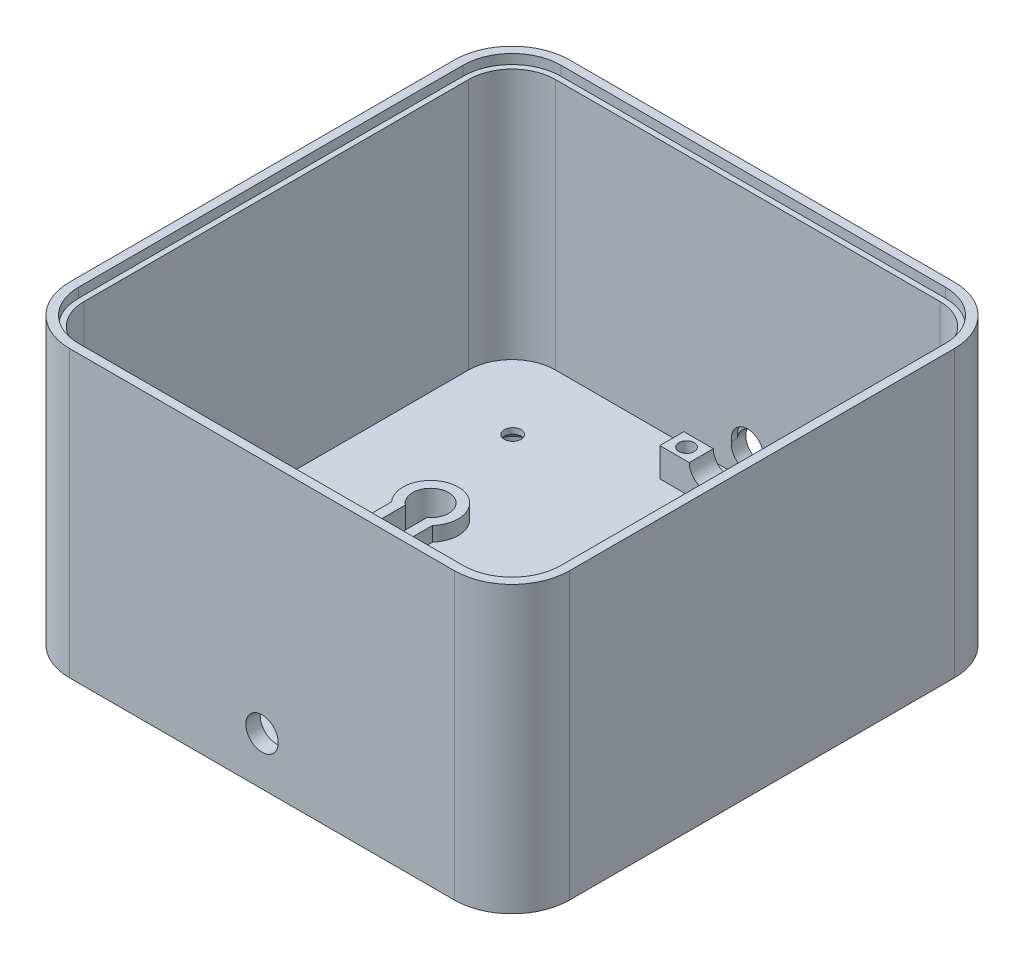
SolidWorks part; units mm, degrees
ref_plane "Alzado" through (0, 0, 0) normal (0, 0, 1) x (1, 0, 0)
ref_plane "Planta" through (0, 0, 0) normal (0, 1, 0) x (1, 0, 0)
ref_plane "Vista lateral" through (0, 0, 0) normal (1, 0, 0) x (0, 0, -1)
sketch "Croquis1" plane through (0, 0, 0) normal (0, 1, 0) x (1, 0, 0)
  line L1 (12, 0) -> (92, 0)
  line L2 (0, 12) -> (0, 92)
  line L3 (12, 104) -> (92, 104)
  line L4 (104, 12) -> (104, 92)
  arc A0 (12, 0) -> (0, 12) centre (12, 12) cw
  arc A1 (92, 0) -> (104, 12) centre (92, 12) ccw
  arc A2 (92, 104) -> (104, 92) centre (92, 92) cw
  arc A3 (0, 92) -> (12, 104) centre (12, 92) cw
  point P7 (0, 0)
  point P10 (104, 0)
  point P15 (0, 104)
  dimension "D3" = 12
  dimension "D1" = 104
  dimension "D2" = 104
extrude "Saliente-Extruir1" add sketch "Croquis1" along normal blind 5
sketch "Croquis2" plane through (0, 5, 0) normal (0, 1, 0) x (1, 0, 0)
  line L0 (12, 3) -> (92, 3)
  line L1 (101, 12) -> (101, 92)
  line L2 (92, 101) -> (12, 101)
  line L3 (3, 92) -> (3, 12)
  line L4 (12, 0) -> (92, 0)
  line L5 (104, 12) -> (104, 92)
  line L6 (92, 104) -> (12, 104)
  line L7 (0, 92) -> (0, 12)
  line L8 (12, 0) -> (92, 0)
  line L9 (104, 12) -> (104, 92)
  line L10 (92, 104) -> (12, 104)
  line L11 (0, 92) -> (0, 12)
  arc A0 (3, 12) -> (12, 3) centre (12, 12) ccw
  arc A1 (92, 3) -> (101, 12) centre (92, 12) ccw
  arc A2 (101, 92) -> (92, 101) centre (92, 92) ccw
  arc A3 (12, 101) -> (3, 92) centre (12, 92) ccw
  arc A4 (0, 12) -> (12, 0) centre (12, 12) ccw
  arc A5 (92, 0) -> (104, 12) centre (92, 12) ccw
  arc A6 (104, 92) -> (92, 104) centre (92, 92) ccw
  arc A7 (12, 104) -> (0, 92) centre (12, 92) ccw
  arc A8 (0, 12) -> (12, 0) centre (12, 12) ccw
  arc A9 (92, 0) -> (104, 12) centre (92, 12) ccw
  arc A10 (104, 92) -> (92, 104) centre (92, 92) ccw
  arc A11 (12, 104) -> (0, 92) centre (12, 92) ccw
  dimension "D1" = 0
  dimension "D2" = 3
extrude "Saliente-Extruir2" add sketch "Croquis2" along normal blind 54.34
sketch "Croquis3" plane through (0, 59.34, 0) normal (0, 1, 0) x (1, 0, 0)
  line L0 (12, 1.85) -> (92, 1.85)
  line L1 (102.15, 12) -> (102.15, 92)
  line L2 (92, 102.15) -> (12, 102.15)
  line L3 (1.85, 92) -> (1.85, 12)
  line L4 (12, 0) -> (92, 0)
  line L5 (104, 12) -> (104, 92)
  line L6 (92, 104) -> (12, 104)
  line L7 (0, 92) -> (0, 12)
  line L8 (12, 0) -> (92, 0)
  line L9 (104, 12) -> (104, 92)
  line L10 (92, 104) -> (12, 104)
  line L11 (0, 92) -> (0, 12)
  arc A0 (1.85, 12) -> (12, 1.85) centre (12, 12) ccw
  arc A1 (92, 1.85) -> (102.15, 12) centre (92, 12) ccw
  arc A2 (102.15, 92) -> (92, 102.15) centre (92, 92) ccw
  arc A3 (12, 102.15) -> (1.85, 92) centre (12, 92) ccw
  arc A4 (0, 12) -> (12, 0) centre (12, 12) ccw
  arc A5 (92, 0) -> (104, 12) centre (92, 12) ccw
  arc A6 (104, 92) -> (92, 104) centre (92, 92) ccw
  arc A7 (12, 104) -> (0, 92) centre (12, 92) ccw
  arc A8 (0, 12) -> (12, 0) centre (12, 12) ccw
  arc A9 (92, 0) -> (104, 12) centre (92, 12) ccw
  arc A10 (104, 92) -> (92, 104) centre (92, 92) ccw
  arc A11 (12, 104) -> (0, 92) centre (12, 92) ccw
  dimension "D1" = 0
  dimension "D2" = 1.85
extrude "Cortar-Extruir1" cut sketch "Croquis3" against normal blind 2 contours A0 L0 A1 L1 A2 L2 A3 L3
sketch "Croquis4" plane through (0, 0, 0) normal (0, -1, 0) x (1, 0, 0)
  line L0 (0, 0) -> (26, 0) construction
  line L1 (12, 0) -> (92, 0) construction
  line L2 (26, 0) -> (26, -50.33) construction
  line L3 (52, 0) -> (52, -86.7959) construction
  line L4 (23.75, -50.33) -> (23.75, -58.07)
  line L5 (28.25, -50.33) -> (28.25, -58.07)
  line L6 (75.75, -50.33) -> (75.75, -58.07)
  line L7 (80.25, -50.33) -> (80.25, -58.07)
  arc A0 (23.75, -58.07) -> (28.25, -58.07) centre (26, -61.07) ccw
  arc A1 (28.25, -50.33) -> (23.75, -50.33) centre (26, -50.33) ccw
  arc A2 (80.25, -58.07) -> (75.75, -58.07) centre (78, -61.07) cw
  arc A3 (75.75, -50.33) -> (80.25, -50.33) centre (78, -50.33) cw
  dimension "D1" = 26
  dimension "D2" = 61.07
extrude "Cortar-Extruir2" cut sketch "Croquis4" against normal blind 17
sketch "Croquis5" plane through (0, 5, 0) normal (0, 1, 0) x (1, 0, 0)
  line L0 (23.75, 50.33) -> (23.75, 58.07) construction
  line L1 (28.25, 58.07) -> (28.25, 50.33) construction
  line L2 (80.25, 58.07) -> (80.25, 50.33) construction
  line L3 (75.75, 50.33) -> (75.75, 58.07) construction
  line L20 (23.75, 50.33) -> (23.75, 58.07)
  line L21 (28.25, 58.07) -> (28.25, 50.33)
  line L22 (80.25, 58.07) -> (80.25, 50.33)
  line L23 (75.75, 50.33) -> (75.75, 58.07)
  line L24 (73.75, 50.33) -> (73.75, 57.197)
  line L25 (82.25, 57.197) -> (82.25, 50.33)
  line L26 (21.75, 50.33) -> (21.75, 57.197)
  line L27 (30.25, 57.197) -> (30.25, 50.33)
  arc A0 (23.75, 50.33) -> (28.25, 50.33) centre (26, 50.33) ccw construction
  arc A1 (28.25, 58.07) -> (23.75, 58.07) centre (26, 61.07) ccw construction
  arc A2 (80.25, 58.07) -> (75.75, 58.07) centre (78, 61.07) ccw construction
  arc A3 (75.75, 50.33) -> (80.25, 50.33) centre (78, 50.33) ccw construction
  arc A20 (23.75, 50.33) -> (28.25, 50.33) centre (26, 50.33) ccw
  arc A21 (28.25, 58.07) -> (23.75, 58.07) centre (26, 61.07) ccw
  arc A22 (80.25, 58.07) -> (75.75, 58.07) centre (78, 61.07) ccw
  arc A23 (75.75, 50.33) -> (80.25, 50.33) centre (78, 50.33) ccw
  arc A24 (82.25, 57.197) -> (73.75, 57.197) centre (78, 61.07) ccw
  arc A25 (73.75, 50.33) -> (82.25, 50.33) centre (78, 50.33) ccw
  arc A26 (30.25, 57.197) -> (21.75, 57.197) centre (26, 61.07) ccw
  arc A27 (21.75, 50.33) -> (30.25, 50.33) centre (26, 50.33) ccw
  dimension "D1" = 2
extrude "Saliente-Extruir3" add sketch "Croquis5" along normal blind 3
sketch "Croquis6" plane through (0, 5, 0) normal (0, 1, 0) x (1, 0, 0)
  line L0 (14.8757, 40.1901) -> (34.6757, 40.1901)
  line L1 (16.8757, 38.1901) -> (32.6757, 38.1901)
  line L2 (16.8757, 38.1901) -> (16.8757, 11.3901)
  line L3 (16.8757, 11.3901) -> (32.6757, 11.3901)
  line L5 (34.6757, 40.1901) -> (34.6757, 38.1901)
  line L6 (14.8757, 9.3901) -> (34.6757, 9.3901)
  line L7 (14.8757, 40.1901) -> (14.8757, 9.3901)
  line L10 (32.6757, 38.1901) -> (34.6757, 38.1901)
  line L11 (32.6757, 11.3901) -> (34.6757, 11.3901)
  line L12 (34.6757, 11.3901) -> (34.6757, 9.3901)
  line L13 (34.6757, 40.1901) -> (34.6757, 9.3901) construction
  line L14 (32.6757, 38.1901) -> (32.6757, 11.3901) construction
  dimension "D1" = 15.8
  dimension "D2" = 26.8
  dimension "D3" = 2
extrude "Saliente-Extruir4" add sketch "Croquis6" along normal blind 15
sketch "Croquis8" plane through (0, 5, 0) normal (0, 1, 0) x (1, 0, 0)
  line L0 (52, 3) -> (52, 18.8903) construction
  line L1 (12, 3) -> (92, 3) construction
  line L2 (42.5, 18.8903) -> (61.5, 18.8903)
  line L3 (61.5, 18.8903) -> (61.5, 23.8903)
  line L4 (61.5, 23.8903) -> (42.5, 23.8903)
  line L5 (52, 23.8903) -> (52, 18.8903) construction
  line L6 (42.5, 18.8903) -> (42.5, 23.8903)
  dimension "D1" = 5
  dimension "D2" = 9.5
extrude "Saliente-Extruir5" add sketch "Croquis8" along normal blind 6
sketch "Croquis10" plane through (0, 0, -23.8903) normal (0, 0, -1) x (-1, 0, 0)
  line L0 (-61.5, 11) -> (-42.5, 11) construction
  circle A0 centre (-52, 11) radius 3.3758
extrude "Cortar-Extruir3" cut sketch "Croquis10" against normal blind 10
sketch "Croquis11" plane through (0, 11, 0) normal (0, 1, 0) x (1, 0, 0)
  line L0 (55.3758, 21.3903) -> (61.5, 21.3903) construction
  line L1 (55.3758, 23.8903) -> (55.3758, 18.8903) construction
  line L2 (61.5, 18.8903) -> (61.5, 23.8903) construction
  line L3 (52, 23.8903) -> (52, 18.8903) construction
  line L4 (55.3758, 23.8903) -> (48.6242, 23.8903) construction
  line L5 (48.6242, 18.8903) -> (55.3758, 18.8903) construction
  circle A0 centre (58.4379, 21.3903) radius 1.6
  circle A1 centre (45.5621, 21.3903) radius 1.6
extrude "Cortar-Extruir4" cut sketch "Croquis11" against normal blind 9
sketch "Croquis12" plane through (0, 0, -3) normal (0, 0, -1) x (-1, 0, 0)
  circle A0 centre (-52, 10) radius 3.3758
extrude "Cortar-Extruir5" cut sketch "Croquis12" against normal blind 9 and the other way blind 138
ref_plane "Plano1" through (0, 0, -58.07) normal (0, 0, -1) x (-1, 0, 0)
mirror "Simetría1" about plane through (0, 0, -58.07) normal (0, 0, -1) of "Cortar-Extruir3", "Cortar-Extruir4", "Saliente-Extruir5"
sketch "Croquis13" plane through (0, 0, 0) normal (0, -1, 0) x (1, 0, 0)
  circle A0 centre (72.9618, -32.5376) radius 4
  circle A1 centre (86.1816, -84.5582) radius 4
  circle A2 centre (19.2106, -84.9387) radius 4
extrude "Cortar-Extruir6" cut sketch "Croquis13" against normal blind 2.2
sketch "Croquis14" plane through (0, 2.2, 0) normal (0, -1, 0) x (1, 0, 0)
  circle A0 centre (72.9618, -32.5376) radius 1.75
  circle A1 centre (86.1816, -84.5582) radius 1.75
  circle A2 centre (19.2106, -84.9387) radius 1.75
extrude "Cortar-Extruir7" cut sketch "Croquis14" against normal blind 18.2
chamfer "Chaflán1" distance 1.75 angle 43 3 edges at (19.2106, 2.2, -86.6887) (86.1816, 2.2, -86.3082) (72.9618, 2.2, -34.2876)
sketch "Croquis15" plane through (0, 5, 0) normal (0, 1, 0) x (1, 0, 0)
  line L0 (30.4225, 31.8383) -> (30.4225, 25.8927)
  line L1 (30.4225, 25.8927) -> (32.9281, 25.8927)
  line L2 (32.9281, 25.8927) -> (32.9281, 31.8383)
  line L3 (32.9281, 31.8383) -> (30.4225, 31.8383)
extrude "Saliente-Extruir6" add sketch "Croquis15" along normal blind 6.2
sketch "Croquis16" plane through (0, 5, 0) normal (0, 1, 0) x (1, 0, 0)
  line L0 (17.6566, 13.1) -> (17.6566, 11.3901)
  line L1 (34.6757, 11.3901) -> (16.8757, 11.3901) construction
  line L2 (20.9791, 13.1) -> (20.9791, 11.3901)
  line L3 (20.9791, 11.3901) -> (17.6566, 11.3901)
  line L4 (24.1855, 36.1073) -> (24.1855, 38.1901)
  line L5 (16.8757, 38.1901) -> (34.6757, 38.1901) construction
  line L6 (24.1855, 38.1901) -> (27.5913, 38.1901)
  line L7 (27.5913, 38.1901) -> (27.5913, 36.1073)
  arc A0 (24.1855, 36.1073) -> (27.5913, 36.1073) centre (25.8884, 36.1073) ccw
  arc A1 (20.9791, 13.1) -> (17.6566, 13.1) centre (19.3179, 13.1) ccw
  circle A2 centre (28.2208, 23.4711) radius 1.5764
  point P1 (28.2208, 23.4711)
  line M22 (16.8757, 11.3901) -> (34.6757, 11.3901)
  line M28 (34.6757, 38.1901) -> (16.8757, 38.1901)
extrude "Saliente-Extruir7" add sketch "Croquis16" along normal blind 2.2 contours L2 A1 L0 M22 | A2 | L4 A0 L7 M28
fillet "Redondeo1" radius 10 2 edges at (34.6757, 20, -39.1901) (34.6757, 20, -10.3901)
